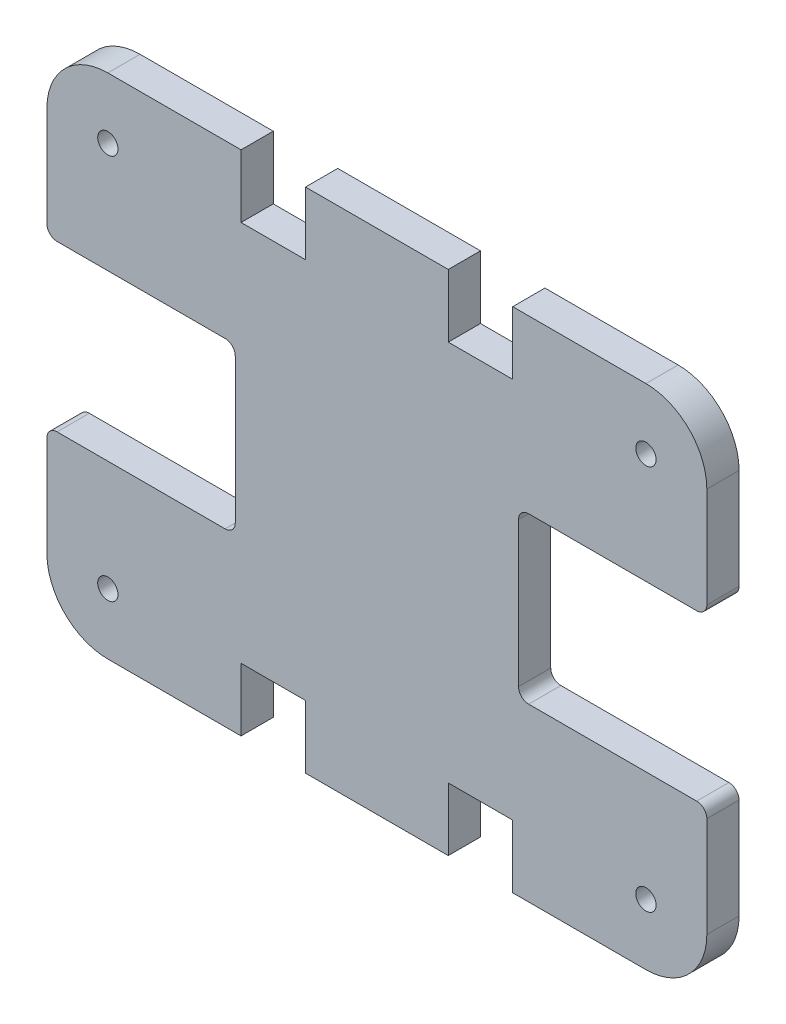
SolidWorks part; units mm, degrees
ref_plane "Front Plane" through (0, 0, 0) normal (0, 0, 1) x (1, 0, 0)
ref_plane "Top Plane" through (0, 0, 0) normal (0, 1, 0) x (1, 0, 0)
ref_plane "Right Plane" through (0, 0, 0) normal (1, 0, 0) x (0, 0, -1)
sketch "overall dimensions" plane through (0, 0, 0) normal (0, 0, 1) x (1, 0, 0)
  line L1 (-32.5, 25) -> (32.5, 25)
  line L2 (-32.5, 25) -> (-32.5, -25)
  line L3 (-32.5, -25) -> (32.5, -25)
  line L4 (32.5, 25) -> (32.5, -25)
  line L5 (-32.5, 25) -> (32.5, -25) construction
  line L6 (-32.5, -25) -> (32.5, 25) construction
  point P0 (0, 0)
  dimension "D1" = 65
  dimension "D2" = 50
extrude "Rectangular Plate" add sketch "overall dimensions" against normal blind 3.175
fillet "External 4 Fillets" radius 6 4 edges at (-32.5, 25, -1.5875) (-32.5, -25, -1.5875) (32.5, -25, -1.5875) (32.5, 25, -1.5875)
sketch "hole positions" plane through (0, 0, 0) normal (0, 0, 1) x (1, 0, 0)
  line L0 (0, -25) -> (0, 25) construction
  line L1 (-26.5, -25) -> (26.5, -25) construction
  line L2 (26.5, 25) -> (-26.5, 25) construction
  line L3 (-32.5, 0) -> (32.5, 0) construction
  line L4 (-32.5, 19) -> (-32.5, -19) construction
  line L5 (32.5, -19) -> (32.5, 19) construction
  circle A0 centre (-26.5, 19) radius 1
  circle A1 centre (26.5, 19) radius 1
  circle A2 centre (26.5, -19) radius 1
  circle A3 centre (-26.5, -19) radius 1
  dimension "D1" = 6
  dimension "D2" = 6
extrude "Corner Holes" cut sketch "hole positions" against normal through all
sketch "RJ45 geometry" plane through (0, 0, 0) normal (0, 0, 1) x (1, 0, 0)
  line L0 (-32.5, 0) -> (32.5, 0) construction
  line L1 (-32.5, 19) -> (-32.5, -19) construction
  line L2 (32.5, -19) -> (32.5, 19) construction
  line L3 (0, 25) -> (0, -25) construction
  line L4 (26.5, 25) -> (-26.5, 25) construction
  line L5 (-26.5, -25) -> (26.5, -25) construction
  line L6 (-13.95, -8.12) -> (-32.5, -8.12)
  line L7 (-13.95, -8.12) -> (-13.95, 8.12)
  line L8 (-32.5, -8.12) -> (-32.5, 8.12)
  line L9 (-13.95, 8.12) -> (-32.5, 8.12)
  line L10 (-13.95, -8.12) -> (-32.5, 8.12) construction
  line L11 (-32.5, -8.12) -> (-13.95, 8.12) construction
  line L12 (32.5, -8.12) -> (32.5, 8.12)
  line L13 (13.95, -8.12) -> (32.5, -8.12)
  line L14 (13.95, -8.12) -> (13.95, 8.12)
  line L15 (13.95, 8.12) -> (32.5, 8.12)
  point P13 (-23.225, 0)
  dimension "D1" = 18.55
  dimension "D2" = 16.24
extrude "RJ45 cutouts" cut sketch "RJ45 geometry" against normal through all
sketch "clip slot geometry" plane through (0, 0, 0) normal (0, 0, 1) x (1, 0, 0)
  line L0 (0, 25) -> (0, -25) construction
  line L1 (26.5, 25) -> (-26.5, 25) construction
  line L2 (-26.5, -25) -> (26.5, -25) construction
  line L3 (-32.375, 0) -> (32.375, 0) construction
  line L4 (13.38, 25) -> (13.38, 18.8)
  line L5 (-13.38, 25) -> (-7.03, 25)
  line L6 (-13.38, 25) -> (-13.38, 18.8)
  line L7 (-13.38, 18.8) -> (-7.03, 18.8)
  line L8 (-7.03, 25) -> (-7.03, 18.8)
  line L9 (13.38, 25) -> (7.03, 25)
  line L10 (7.03, 25) -> (7.03, 18.8)
  line L11 (13.38, 18.8) -> (7.03, 18.8)
  line L12 (-13.38, -25) -> (-7.03, -25)
  line L13 (-13.38, -25) -> (-13.38, -18.8)
  line L14 (-13.38, -18.8) -> (-7.03, -18.8)
  line L15 (-7.03, -25) -> (-7.03, -18.8)
  line L16 (13.38, -18.8) -> (7.03, -18.8)
  line L17 (7.03, -25) -> (7.03, -18.8)
  line L18 (13.38, -25) -> (7.03, -25)
  line L19 (13.38, -25) -> (13.38, -18.8)
  dimension "D1" = 6.35
  dimension "D2" = 6.2
  dimension "D3" = 7.03
extrude "clip slots" cut sketch "clip slot geometry" against normal through all
fillet "Fillet1" radius 1 8 edges at (32.5, -8.12, -1.5875) (32.5, 8.12, -1.5875) (13.95, 8.12, -1.5875) (13.95, -8.12, -1.5875) (-13.95, 8.12, -1.5875) (-32.5, 8.12, -1.5875) (-13.95, -8.12, -1.5875) (-32.5, -8.12, -1.5875)
sketch "Sketch1" plane through (0, 0, -3.175) normal (0, 0, -1) x (-1, 0, 0)
  line L1 (26.5, -19) -> (-26.5, -19) construction
  line L2 (26.5, -19) -> (26.5, 19) construction
  line L3 (26.5, 19) -> (-26.5, 19) construction
  line L4 (-26.5, -19) -> (-26.5, 19) construction
  line L5 (26.5, -19) -> (-26.5, 19) construction
  line L6 (26.5, 19) -> (-26.5, -19) construction
  point P0 (0, 0)
